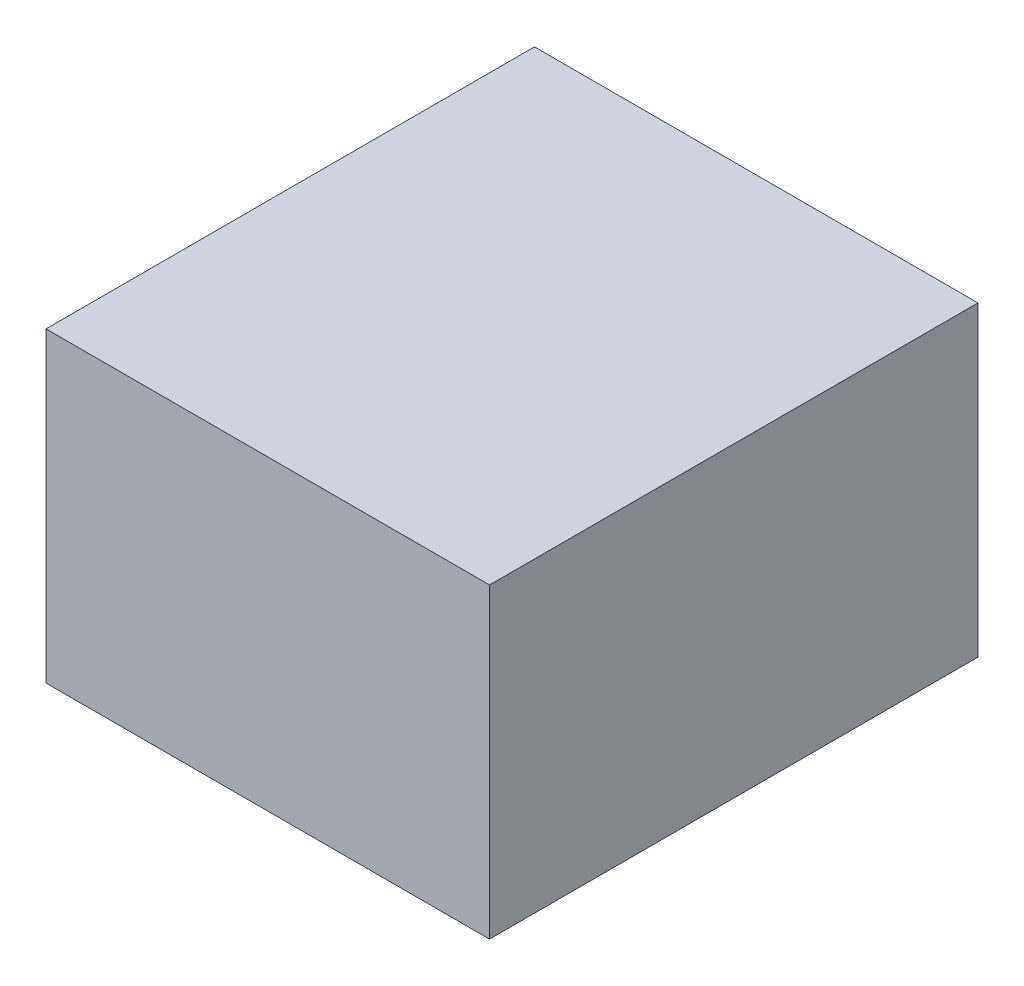
SolidWorks part; units mm, degrees
ref_plane "Front Plane" through (0, 0, 0) normal (0, 0, 1) x (1, 0, 0)
ref_plane "Top Plane" through (0, 0, 0) normal (0, 1, 0) x (1, 0, 0)
ref_plane "Right Plane" through (0, 0, 0) normal (1, 0, 0) x (0, 0, -1)
sketch "Sketch1" plane through (0, 0, 0) normal (0, 1, 0) x (1, 0, 0)
  line L1 (-45.4, -50) -> (45.4, -50)
  line L2 (-45.4, -50) -> (-45.4, 50)
  line L3 (-45.4, 50) -> (45.4, 50)
  line L4 (45.4, -50) -> (45.4, 50)
  line L5 (-45.4, -50) -> (45.4, 50) construction
  line L6 (-45.4, 50) -> (45.4, -50) construction
  point P0 (0, 0)
extrude "Boss-Extrude1" add sketch "Sketch1" along normal blind 62.8
